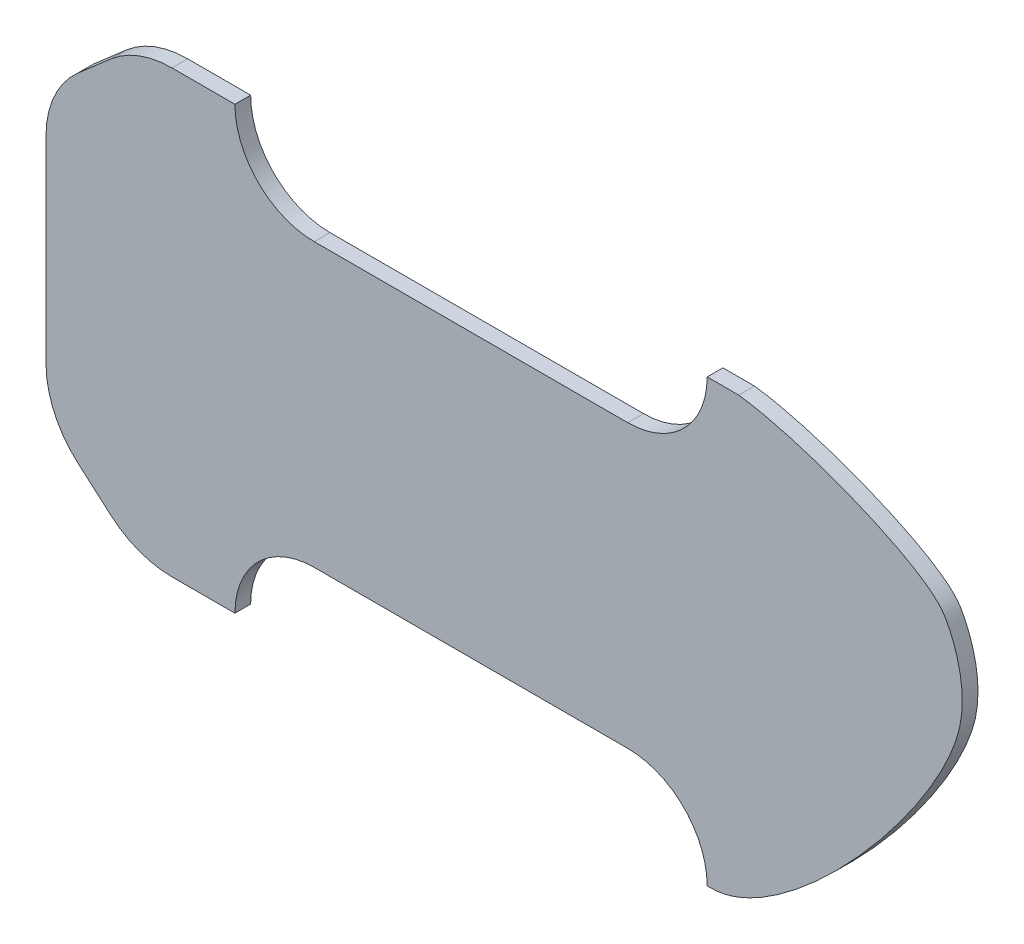
SolidWorks part; units mm, degrees
material "3.0205 (EN AW-1200)"
ref_plane "Plan de face" through (0, 0, 0) normal (0, 0, 1) x (1, 0, 0)
ref_plane "Plan de dessus" through (0, 0, 0) normal (0, 1, 0) x (1, 0, 0)
ref_plane "Plan de droite" through (0, 0, 0) normal (1, 0, 0) x (0, 0, -1)
sketch "Esquisse1" plane through (0, 0, 0) normal (0, 0, 1) x (1, 0, 0)
  line L0 (-77.472, 59.5843) -> (-97.472, 59.5843)
  line L1 (-116.9386, 52.289) -> (-127.3186, 43.2376)
  line L2 (-77.472, -80.4157) -> (-97.472, -80.4157)
  line L3 (-116.9369, -73.1217) -> (-127.3169, -64.0717)
  line L4 (72.528, 59.5843) -> (82.528, 59.5843)
  line L5 (-137.4714, -41.7463) -> (-137.4714, 20.9136)
  line L7 (-52.272, 34.3843) -> (47.328, 34.3843)
  line L9 (72.528, -80.4157) -> (73.528, -80.4157)
  line L13 (-52.272, -55.2157) -> (47.328, -55.2157)
  arc A0 (-116.9386, 52.289) -> (-97.472, 59.5843) centre (-97.472, 29.9649) cw
  arc A1 (-137.4714, 20.9136) -> (-127.3186, 43.2376) centre (-107.852, 20.9136) cw
  arc A2 (-127.3169, -64.0717) -> (-137.4714, -41.7463) centre (-107.852, -41.7463) cw
  arc A3 (-97.472, -80.4157) -> (-116.9369, -73.1217) centre (-97.472, -50.7963) cw
  arc A4 (-77.472, 59.5843) -> (-52.272, 34.3843) centre (-52.272, 59.5843) ccw
  arc A5 (-77.472, -80.4157) -> (-52.272, -55.2157) centre (-52.272, -80.4157) cw
  arc A6 (72.528, -80.4157) -> (47.328, -55.2157) centre (47.328, -80.4157) ccw
  arc A7 (72.528, 59.5843) -> (47.328, 34.3843) centre (47.328, 59.5843) cw
  spline S0 degree 3 poles (82.528, 59.5843) (101.2949, 57.3452) (142.4689, 41.5905) (150.7228, 26.7589) (154.2341, 16.0172) (151.3643, -18.5968) (97.2752, -80.832) (73.528, -80.4157) knots 0 0 0 0 0.313333 0.364624 0.496436 0.561622 1 1 1 1
  point P6 (-108.5723, 59.5843)
  point P21 (-137.4714, 34.3843)
  point P27 (-108.5711, -80.4157)
  dimension "D16" = 80
  dimension "D17" = 63
  dimension "D18" = 29.6194
  dimension "D19" = 29.6194
  dimension "D9" = 25.2
  dimension "D28" = 25.2
  dimension "D25" = 25.2
  dimension "D30" = 25.2
  dimension "D8" = 56
  dimension "D12" = 29.6194
  dimension "D20" = 29.6194
  dimension "D33" = 99.6
  dimension "D4" = 140
  dimension "D5" = 25.2
  dimension "D6" = 1
  dimension "D7" = 66
  dimension "D10" = 150
  dimension "D11" = 21
  dimension "D13" = 10
  dimension "D14" = 90
  dimension "D15" = 20
  dimension "D21" = 150
  dimension "D23" = 99.6
  dimension "D24" = 20
  dimension "D26" = 25.2
  dimension "D27" = 25.2
  dimension "D29" = 9.05
  dimension "D31" = 25.2
  dimension "D32" = 10.38
extrude "Boss.-Extru.1" add sketch "Esquisse1" along normal blind 5
